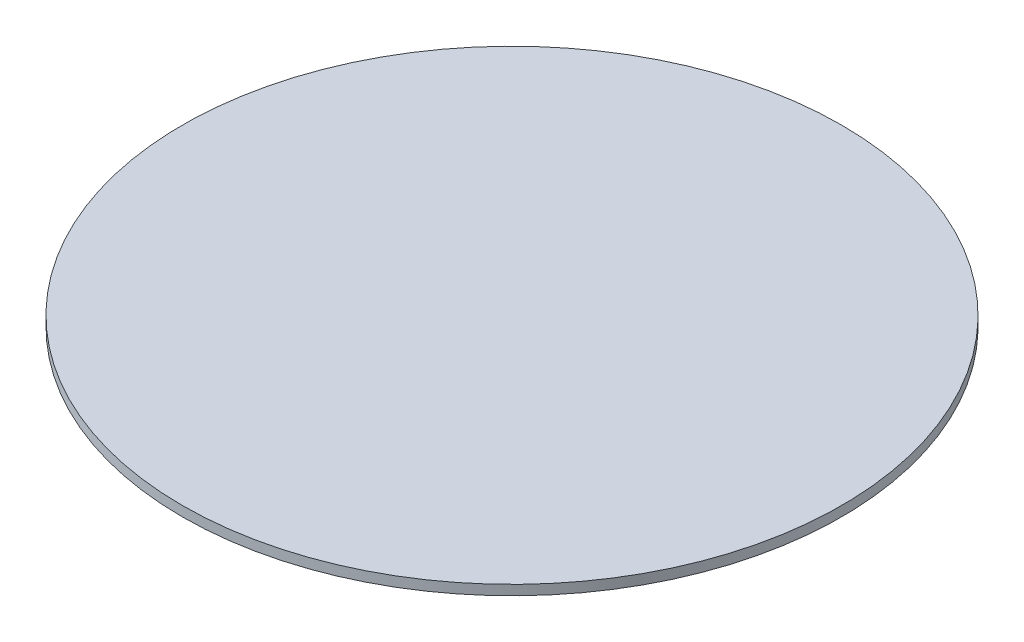
SolidWorks part; units mm, degrees
material "A-Glass Fiber"
ref_plane "Front Plane" through (0, 0, 0) normal (0, 0, 1) x (1, 0, 0)
ref_plane "Top Plane" through (0, 0, 0) normal (0, 1, 0) x (1, 0, 0)
ref_plane "Right Plane" through (0, 0, 0) normal (1, 0, 0) x (0, 0, -1)
sketch "Sketch1" plane through (0, 0, 0) normal (0, 1, 0) x (1, 0, 0)
  circle A0 centre (0, 0) radius 20
  dimension "D1" = 40
extrude "PCB" add sketch "Sketch1" along normal blind 0.6
sketch "Sketch2" plane through (0, 0.6, 0) normal (0, 1, 0) x (1, 0, 0)
  line L0 (0, 20) -> (0, 0) construction
  line L1 (-9, 16) -> (9, 16)
  line L2 (-9, 16) -> (-9, 12)
  line L3 (-9, 12) -> (9, 12)
  line L4 (9, 16) -> (9, 12)
  circle A0 centre (0, 0) radius 20 construction
  point P9 (0, 16)
  dimension "D1" = 4
  dimension "D2" = 18
  dimension "D3" = 16
